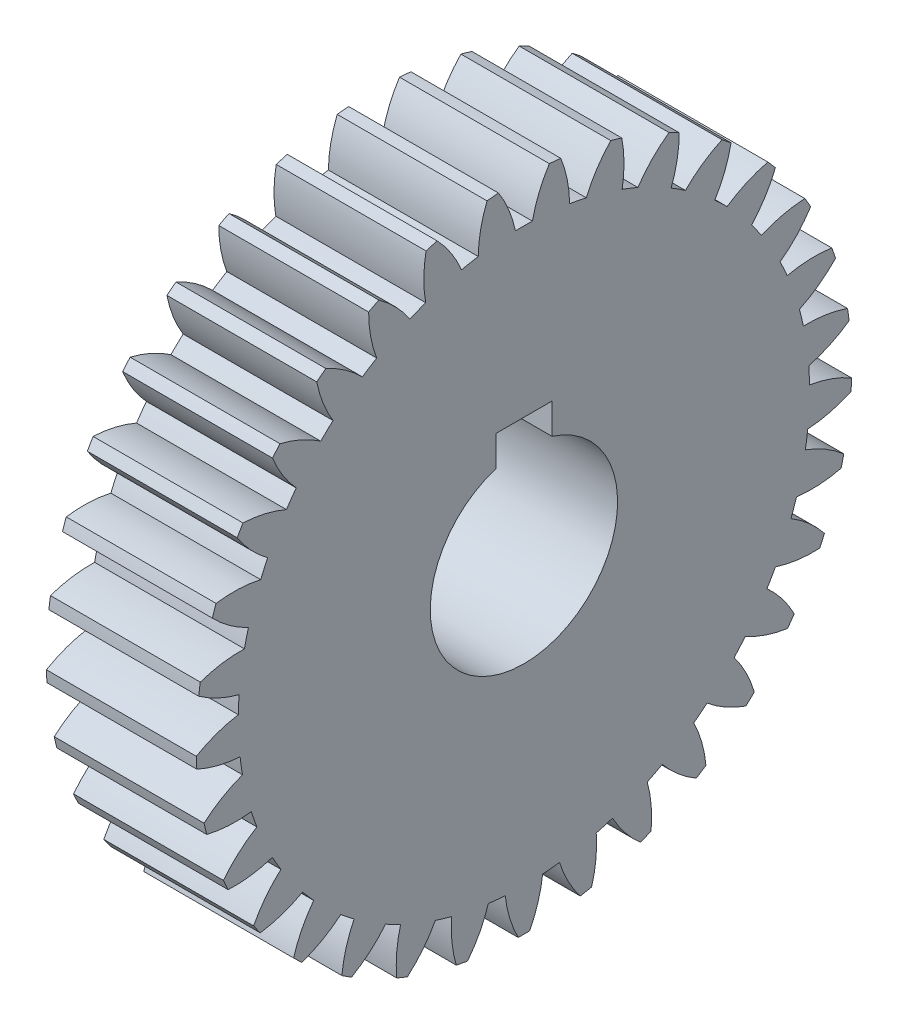
SolidWorks part; units mm, degrees
ref_plane "Plane1" through (0, 0, 0) normal (0, 0, 1) x (1, 0, 0)
ref_plane "Plane2" through (0, 0, 0) normal (0, 1, 0) x (1, 0, 0)
ref_plane "Plane3" through (0, 0, 0) normal (1, 0, 0) x (0, 0, -1)
sketch "HoldingSke" plane through (0, 0, 0) normal (0, 1, 0) x (1, 0, 0)
  line L0 (0, 0) -> (0.4193, -0.2723)
  line L1 (-15, 0) -> (100, 0) construction
  line L2 (0, 0) -> (-2.1039, 2.3779)
  line L3 (0, 0) -> (-11.863, 4.5341)
  line L4 (0, 0) -> (7.2428, 4.7035)
  line L5 (0, 0) -> (-46.8476, -17.4728)
  line L6 (0, 0) -> (-13.2634, -8.9489)
  line L7 (-2.1039, 2.3779) -> (8.6586, 51.2059)
  line L8 (-76.2, 54.61) -> (-73.4, 54.61)
  line L9 (-71.009, 38.7566) -> (-53.1078, 45.2721)
  line L10 (-76.2, 71.12) -> (104.1128, 71.12)
  line L11 (0, 0) -> (-16, 0)
  line L12 (-76.2, 101.6) -> (-76.133, 101.6)
  line L13 (24.9733, 27.94) -> (52.9518, 28.4284)
  line L14 (24.9733, 27.94) -> (24.9743, 27.94)
  line L15 (24.9733, 27.94) -> (100.4006, 29.5858)
  line L16 (-63.627, -2) -> (-12.827, -2)
  circle A0 centre (0, 0) radius 10
  circle A1 centre (0, 0) radius 30.499
  circle A2 centre (0, 0) radius 37.5
  circle A3 centre (0, 0) radius 10
  dimension "MHD" = 60.998
  dimension "Hub_dia" = 75
  dimension "Bore" = 20
  dimension "MBD" = 20
  dimension "Num_teeth" = 33
  dimension "Pitch" = 0.5
  dimension "Overall_len" = 50
  dimension "Show_teeth" = 33
  dimension "Thickness" = 16
  dimension "OAL" = 50.0001
  dimension "T_dim" = 2.8
  dimension "Ap" = 20
  dimension "H" = 19.05
  dimension "Pitch_radius" = 180.3128
  dimension "Width" = 16
  dimension "Backlash" = 0.067
  dimension "Addendum_fac" = 1
  dimension "Dedendum_fac" = 1.25
  dimension "Clearance_fac" = 0.25
  dimension "Dedendum_add" = 0.001
  dimension "Module" = 2
sketch "BasProSke" plane through (0, 0, 0) normal (0, 1, 0) x (1, 0, 0)
  line L0 (-10, 0) -> (60, 0) construction
  line L1 (0, 0) -> (0, 35)
  line L2 (0, 0) -> (16, 0)
  line L3 (16, 0) -> (16, 35)
  line L4 (16, 35) -> (0, 35)
  dimension "Thickness" = 16
  dimension "Diameter" = 70
revolve "Base-Revolve" add sketch "BasProSke" angle 360 about L0
sketch "TooCutSke" plane through (0, 0, 0) normal (1, 0, 0) x (0, 0, -1)
  line L1 (0, 0) -> (0, 107) construction
  line L2 (0, 0) -> (-1.6874, 32.9568) construction
  line L3 (0, 0) -> (-6.2676, 65.6374) construction
  line L4 (-1.6874, 32.9568) -> (-3.1338, 32.8187) construction
  arc A0 (0.9057, 30.4855) -> (-0.9057, 30.4855) centre (0, 0) ccw
  arc A1 (2.7313, 34.9187) -> (-2.7313, 34.9187) centre (0, 0) ccw
  circle A2 centre (0, 0) radius 33 construction
  circle A3 centre (0, 0) radius 31.0099 construction
  arc A4 (-0.9057, 30.4855) -> (-2.7313, 34.9187) centre (-13.8212, 27.7594) ccw
  arc A5 (2.7313, 34.9187) -> (0.9057, 30.4855) centre (13.8212, 27.7594) ccw
  dimension "Root_dia" = 60.998
  dimension "Overcut_dia" = 70.0508
  dimension "Pitch_dia" = 66
  dimension "Base_dia" = 62.0197
  dimension "Flank_rad" = 13.2
  dimension "Half_ang" = 5.455
  dimension "Half_CT" = 1.453
extrude "ToothCut" cut sketch "TooCutSke" along normal through all
fillet "Breaks" [suppressed] radius 0.04
fillet "RootFillets" [suppressed] radius 0.501
pattern_circular "TeethCuts" count 33 every 10.909 about axis through (-10, 0, 0) along (1, 0, 0) of "ToothCut", "RootFillets", "Breaks"
sketch "HubNeaOneSke" plane through (0, 0, 0) normal (-1, 0, 0) x (0, 0, 1)
  circle A0 centre (0, 0) radius 30.499
  dimension "Diameter" = 60.998
extrude "HubNearOne" [suppressed] add sketch "HubNeaOneSke" along normal blind 34.0001
sketch "HubNeaBotSke" plane through (0, 0, 0) normal (-1, 0, 0) x (0, 0, 1)
  circle A0 centre (0, 0) radius 30.499
  dimension "Diameter" = 60.998
extrude "HubNearBoth" [suppressed] add sketch "HubNeaBotSke" along normal blind 17
ref_plane "FarPln" through (16, 0, 0) normal (1, 0, 0) x (0, 0, -1)
sketch "HubFarSke" plane through (16, 0, 0) normal (1, 0, 0) x (0, 0, -1)
  circle A0 centre (0, 0) radius 30.499
  dimension "Diameter" = 60.998
extrude "HubFar" [suppressed] add sketch "HubFarSke" along normal blind 17
sketch "BorSke" plane through (0, 0, 0) normal (1, 0, 0) x (0, 0, -1)
  circle A0 centre (0, 0) radius 10
  dimension "Diameter" = 20
extrude "Bore" cut sketch "BorSke" along normal mid plane 100.0001
sketch "KeySke" plane through (0, 0, 0) normal (1, 0, 0) x (0, 0, -1)
  line L0 (-3, 0) -> (-3, 12.8)
  line L1 (-3, 12.8) -> (3, 12.8)
  line L2 (3, 12.8) -> (3, 0)
  line L3 (0, 0) -> (0, 34) construction
  line L4 (-3, 0) -> (3, 0)
  dimension "Offset" = 12.8
  dimension "Width" = 6
extrude "Keyway" cut sketch "KeySke" along normal mid plane 100.0001
pattern_circular "Keyway2" [suppressed] count 2 every 90 about axis through (-10, 0, 0) along (1, 0, 0)
equation "' \"Module@HoldingSke\" = 6.35"
equation "' \"Num_teeth@HoldingSke\" = 12"
equation "' \"Ap@HoldingSke\" =  20"
equation "' \"Ap@HoldingSke\" = 20"
equation "' \"Width@HoldingSke\" = 0.5 * 25.4"
equation "' \"Hub_dia@HoldingSke\"= 1 * 25.4"
equation "' \"Hub_dia@HoldingSke\" = 1 * 25.4"
equation "' \"Overall_len@HoldingSke\" = 1.0 * 25.4"
equation "' \"Bore@HoldingSke\" = 0.75 * 25.4"
equation "' \"T_dim@HoldingSke\" = 0.1 * 25.4"
equation "' \"Width@KeySke\" = 0.25 * 25.4"
equation "' \"Show_teeth@HoldingSke\" = 13"
equation "' \"Backlash@HoldingSke\" = 0.009 * 25.4"
equation "' \"Addendum_fac@HoldingSke\" = 1.0"
equation "' \"Dedendum_fac@HoldingSke\" = 1.25"
equation "' \"Dedendum_add@HoldingSke\" = 0.00005 * 25.4"
equation "' \"Clearance_fac@HoldingSke\" = 0.25"
equation "\"Pitch@HoldingSke\" = 1 / \"Module@HoldingSke\""
equation "\"Overcut_dia@TooCutSke\" = (\"Num_teeth@HoldingSke\" + 2 * \"Addendum_fac@HoldingSke\") / \"Pitch@HoldingSke\" + 0.002 * 25.4"
equation "\"Pitch_dia@TooCutSke\" = \"Num_teeth@HoldingSke\" / \"Pitch@HoldingSke\""
equation "\"Base_dia@TooCutSke\" = \"Num_teeth@HoldingSke\" / \"Pitch@HoldingSke\" * cos((\"Ap@HoldingSke\"  * 3.14159265 / 180))"
equation "\"Root_dia@TooCutSke\" = (\"Num_teeth@HoldingSke\" + 2) / \"Pitch@HoldingSke\" - 2 * (\"Addendum_fac@HoldingSke\" + \"Dedendum_fac@HoldingSke\") / \"Pitch@HoldingSke\" - \"Dedendum_add@HoldingSke\" * 2"
equation "\"Half_ang@TooCutSke\" = 180 / \"Num_teeth@HoldingSke\""
equation "\"Half_CT@TooCutSke\" = \"Num_teeth@HoldingSke\" / \"Pitch@HoldingSke\" * sin((3.14159265 / 2 / \"Num_teeth@HoldingSke\")) / 2 - 7 * \"Backlash@HoldingSke\" / 4"
equation "\"Flank_rad@TooCutSke\" = \"Num_teeth@HoldingSke\" / \"Pitch@HoldingSke\" / 5"
equation "\"Radius@RootFillets\" = \"Clearance_fac@HoldingSke\" / \"Pitch@HoldingSke\" + \"Dedendum_add@HoldingSke\""
equation "\"Break_rad@Breaks\" = 0.02 / \"Pitch@HoldingSke\""
equation "\"Thickness@HoldingSke\" = \"Width@HoldingSke\""
equation "\"OAL@HoldingSke\" = \"Thickness@HoldingSke\""
equation "\"MHD@HoldingSke\" = (\"Num_teeth@HoldingSke\" + 2) / \"Pitch@HoldingSke\" - 2 * (\"Addendum_fac@HoldingSke\" + \"Dedendum_fac@HoldingSke\")  / \"Pitch@HoldingSke\" - \"Dedendum_add@HoldingSke\" * 2"
equation "\"MBD@HoldingSke\" = (\"Num_teeth@HoldingSke\" + 2) / \"Pitch@HoldingSke\" - 2 * (\"Addendum_fac@HoldingSke\" + \"Dedendum_fac@HoldingSke\")  / \"Pitch@HoldingSke\" - \"Dedendum_add@HoldingSke\" * 2 - 0.002 * 25.4"
equation "\"MHD@HoldingSke\" = ((sgn( \"MHD@HoldingSke\" - \"Hub_dia@HoldingSke\" )-1)*( \"MHD@HoldingSke\" - \"Hub_dia@HoldingSke\" ))/-2+ \"Hub_dia@HoldingSke\""
equation "\"MBD@HoldingSke\" = ((sgn( \"MBD@HoldingSke\" - \"Bore@HoldingSke\" )-1)*( \"MBD@HoldingSke\" - \"Bore@HoldingSke\" ))/-2+ \"Bore@HoldingSke\""
equation "\"OAL@HoldingSke\" = ((sgn( \"OAL@HoldingSke\" - \"Overall_len@HoldingSke\" )+1)*( \"OAL@HoldingSke\" - \"Overall_len@HoldingSke\" ))/2 + \"Overall_len@HoldingSke\" + 0.000002 * 25.4"
equation "\"Num_teeth@TeethCuts\" = int( \"Show_teeth@HoldingSke\" ) + 1"
equation "\"Num_teeth@TeethCuts\" = ((sgn( \"Num_teeth@TeethCuts\" - \"Num_teeth@HoldingSke\" )-1)*( \"Num_teeth@TeethCuts\" - \"Num_teeth@HoldingSke\" ))/-2+ \"Num_teeth@HoldingSke\""
equation "\"Num_teeth@TeethCuts\" = ((sgn( \"Num_teeth@TeethCuts\" - 2.0)+1)*( \"Num_teeth@TeethCuts\" - 2.0))/2 +2.0"
equation "\"Angle@TeethCuts\" = 360.0 / \"Num_teeth@HoldingSke\""
equation "\"Diameter@BasProSke\" = (\"Num_teeth@HoldingSke\" + 2 * \"Addendum_fac@HoldingSke\") / \"Pitch@HoldingSke\""
equation "\"Thickness@BasProSke\"  = \"Thickness@HoldingSke\""
equation "' \"Fillet_rad@BasProSke\" =  \"Thickness@HoldingSke\" * 0.05"
equation "' \"Fillet_rad@BasProSke\" = \"Thickness@HoldingSke\" * 0.05"
equation "\"MHD@HoldingSke\" = ((sgn( \"MHD@HoldingSke\" - \"Root_dia@TooCutSke\" )-1)*( \"MHD@HoldingSke\" - \"Root_dia@TooCutSke\" ))/-2+ \"Root_dia@TooCutSke\""
equation "\"Diameter@HubNeaOneSke\" = \"MHD@HoldingSke\""
equation "\"Length@HubNearOne\" = \"OAL@HoldingSke\" - \"Thickness@BasProSke\""
equation "\"Diameter@HubNeaBotSke\" = \"MHD@HoldingSke\""
equation "\"Length@HubNearBoth\" = ( \"OAL@HoldingSke\" - \"Thickness@BasProSke\" ) / 2.0"
equation "\"Thickness@FarPln\" = \"Thickness@BasProSke\""
equation "\"Diameter@HubFarSke\" = \"MHD@HoldingSke\""
equation "\"Length@HubFar\" = ( \"OAL@HoldingSke\" - \"Thickness@BasProSke\" ) / 2.0"
equation "\"Diameter@BorSke\" = \"MBD@HoldingSke\""
equation "\"D1@Bore\" = \"OAL@HoldingSke\" * 2.0"
equation "\"D1@Keyway\" = \"OAL@HoldingSke\" * 2.0"
equation "\"Offset@KeySke\" = \"T_dim@HoldingSke\" + \"MBD@HoldingSke\" / 2.0"
